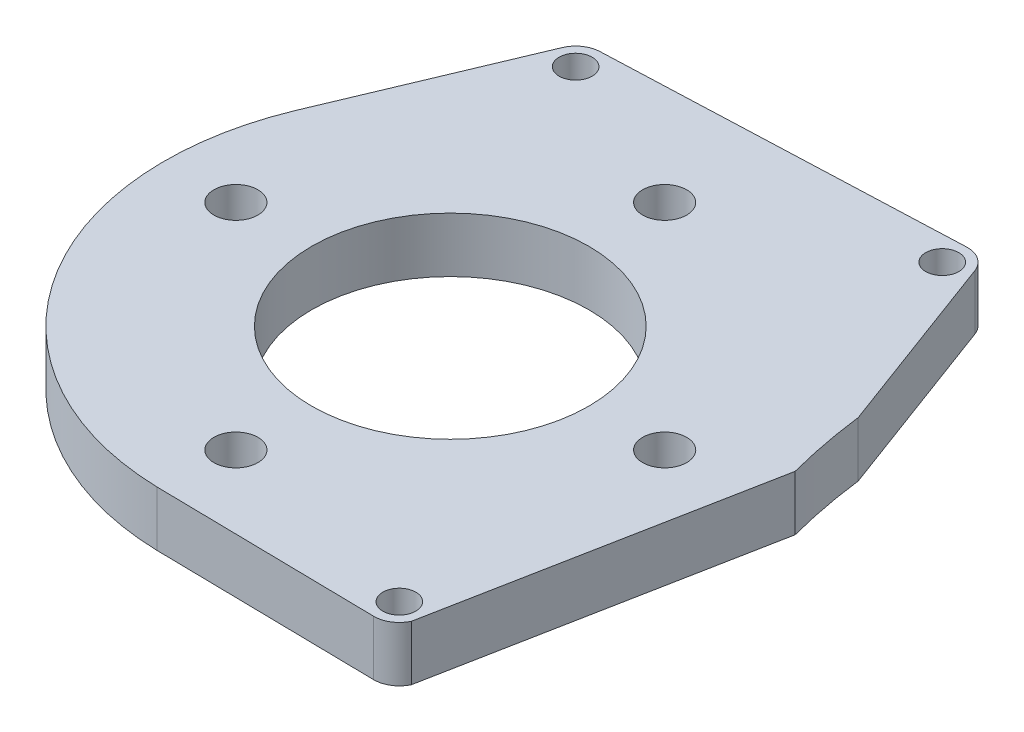
SolidWorks part; units mm, degrees
ref_plane "前视基准面" through (0, 0, 0) normal (0, 0, 1) x (1, 0, 0)
ref_plane "上视基准面" through (0, 0, 0) normal (0, 1, 0) x (1, 0, 0)
ref_plane "右视基准面" through (0, 0, 0) normal (1, 0, 0) x (0, 0, -1)
sketch "Sketch1" plane through (0, 0, 0) normal (0, 1, 0) x (1, 0, 0)
  line L1 (17.33, 31.2256) -> (-14.9001, 29.9396)
  line L3 (28.6531, 4.3097) -> (22.9185, -25.4529)
  line L9 (-25.4357, 10.4807) -> (-18.2449, 27.6141)
  line L11 (27.2164, 11.7149) -> (20.8902, 28.7474)
  line L12 (-0.728, -27.5007) -> (19.3179, -27.833)
  line L14 (-0.6956, -26.001) -> (19.3427, -26.3332)
  line L15 (27.1151, 4.2559) -> (21.477, -25.0063)
  line L16 (25.7488, 11.3581) -> (19.4841, 28.2252)
  line L17 (17.3553, 29.7254) -> (-14.839, 28.4408)
  line L18 (-24.0506, 9.9048) -> (-16.8618, 27.0337)
  circle A1 centre (0, 0) radius 19.5 construction
  circle A2 centre (0, 19.5) radius 2
  circle A3 centre (19.5, 0) radius 2
  circle A4 centre (0, -19.5) radius 2
  circle A5 centre (-19.5, 0) radius 2
  circle A6 centre (0, 0) radius 12.6
  arc A10 (27.2164, 11.7149) -> (28.6531, 4.3097) centre (79.3406, 17.9856) ccw
  arc A23 (-25.4357, 10.4807) -> (-0.728, -27.5007) centre (0, 0) ccw
  circle A36 centre (19.3812, -24.015) radius 1.5
  circle A37 centre (17.3262, 27.4237) radius 1.5
  circle A38 centre (-14.7421, 26.144) radius 1.5
  arc A39 (-14.9001, 29.9396) -> (-18.2449, 27.6141) centre (-14.7421, 26.144) ccw
  arc A40 (17.33, 31.2256) -> (20.8902, 28.7474) centre (17.3262, 27.4237) cw
  arc A41 (22.9185, -25.4529) -> (19.3179, -27.833) centre (19.3812, -24.015) cw
  arc A42 (21.477, -25.0063) -> (19.3427, -26.3332) centre (19.3812, -24.015) cw
  arc A43 (25.7488, 11.3581) -> (27.1151, 4.2559) centre (79.3406, 17.9856) ccw
  arc A44 (17.3553, 29.7254) -> (19.4841, 28.2252) centre (17.3262, 27.4237) cw
  arc A45 (-14.839, 28.4408) -> (-16.8618, 27.0337) centre (-14.7421, 26.144) ccw
  arc A46 (-24.0506, 9.9048) -> (-0.6956, -26.001) centre (0, 0) ccw
  point P14 (0, 0)
  dimension "D1" = 1.5
  dimension "D2" = 39
  dimension "D3" = 4
  dimension "D5" = 25.2
  dimension "D9" = 105
  dimension "D4" = 4
extrude "Boss-Extrude1" add sketch "Sketch1" along normal blind 5
